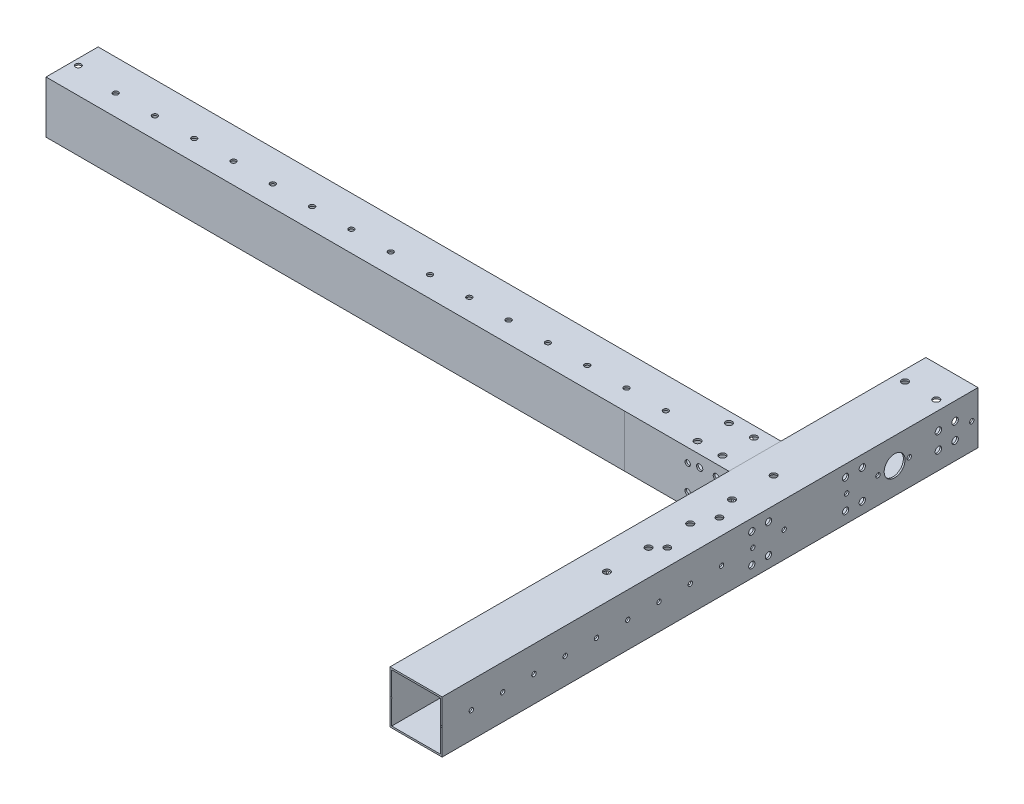
SolidWorks part; units mm, degrees
material "6061 合金"
ref_plane "前视基准面" through (0, 0, 0) normal (0, 0, 1) x (1, 0, 0)
ref_plane "上视基准面" through (0, 0, 0) normal (0, 1, 0) x (1, 0, 0)
ref_plane "右视基准面" through (0, 0, 0) normal (1, 0, 0) x (0, 0, -1)
sketch3d "3D草图1"
  line L0 (0, 0, -82) -> (0, 0, 175)
  line L1 (0, 0, 0) -> (-340, 0, 0)
  dimension "D1" = 175
  dimension "D2" = 340
  dimension "D3" = 82
other "方形管 20X20X1(1)"
ref_plane "基准面1" through (0, 0, 0) normal (-1, 0, 0) x (0, 0, 1)
sketch "草图1" plane through (0, 0, 0) normal (-1, 0, 0) x (0, 0, 1)
  line L0 (-11.7, 11.7) -> (11.7, 11.7)
  line L1 (-12.5, 12.5) -> (12.5, 12.5)
  line L2 (-12.5, 12.5) -> (-12.5, -12.5)
  line L3 (-12.5, -12.5) -> (12.5, -12.5)
  line L4 (12.5, 12.5) -> (12.5, -12.5)
  line L5 (-12.5, 12.5) -> (12.5, -12.5) construction
  line L6 (-12.5, -12.5) -> (12.5, 12.5) construction
  line L7 (11.7, 11.7) -> (11.7, -11.7)
  line L8 (-11.7, -11.7) -> (11.7, -11.7)
  line L9 (-11.7, 11.7) -> (-11.7, -11.7)
  point P0 (0, 0)
  point P10 (0, 0)
  dimension "D1" = 25
  dimension "D2" = 0.8
sketch "草图6" plane through (12.5, 0, 0) normal (1, 0, 0) x (0, 0, -1)
  line L0 (-236, 0) -> (-251, 0) construction
  line L1 (64, 0) -> (67.4326, 0) construction
  line L2 (82, 12.5) -> (82, -12.5) construction
  line L3 (12.5, 12.5) -> (12.5, -12.5) construction
  circle A0 centre (-236, 0) radius 1.05
  circle A1 centre (-221, 0) radius 1.05
  circle A2 centre (-206, 0) radius 1.05
  circle A3 centre (-191, 0) radius 1.05
  circle A4 centre (-176, 0) radius 1.05
  circle A5 centre (-161, 0) radius 1.05
  circle A6 centre (-146, 0) radius 1.05
  circle A7 centre (-131, 0) radius 1.05
  circle A8 centre (-116, 0) radius 1.05
  circle A9 centre (-101, 0) radius 1.05
  circle A10 centre (-86, 0) radius 1.05
  circle A11 centre (-71, 0) radius 1.05
  circle A12 centre (-56, 0) radius 1.05
  circle A13 centre (-41, 0) radius 1.05
  circle A14 centre (-26, 0) radius 1.05
  circle A15 centre (-11, 0) radius 1.05
  circle A16 centre (4, 0) radius 1.05 construction
  circle A17 centre (19, 0) radius 1.05
  circle A18 centre (34, 0) radius 1.05
  circle A19 centre (49, 0) radius 1.05
  circle A20 centre (64, 0) radius 1.05 construction
  circle A21 centre (79, 0) radius 1.05
  circle A22 centre (94, 0) radius 1.05
  circle A23 centre (109, 0) radius 1.05
  circle A24 centre (124, 0) radius 1.05
  circle A25 centre (139, 0) radius 1.05
  circle A26 centre (154, 0) radius 1.05
  circle A27 centre (169, 0) radius 1.05
  circle A29 centre (-251, 0) radius 1.05
  circle A35 centre (-266, 0) radius 1.05
  circle A36 centre (-281, 0) radius 1.05
  circle A37 centre (-296, 0) radius 1.05
  circle A38 centre (71, 4) radius 1.55
  circle A39 centre (63, 4) radius 1.55
  circle A40 centre (71, -4) radius 1.55
  circle A41 centre (63, -4) radius 1.55
  circle A42 centre (42, 0) radius 5
  dimension "D2" = 2.1
  dimension "D7" = 8
  dimension "D10" = 3.1
  dimension "D11" = 10
  dimension "D1" = 3
  dimension "D4" = 15
  dimension "D5" = 5
  dimension "D6" = 15
  dimension "D9" = 4
  dimension "D8" = 8
  dimension "D12" = 29.5
  dimension "D3" = 28
extrude "切除-拉伸5" cut sketch "草图6" against normal through all
sketch "草图7" plane through (0, -12.5, 0) normal (0, -1, 0) x (1, 0, 0)
  line L0 (12.5, 46.5) -> (0, 46.5) construction
  line L1 (12.5, 175) -> (12.5, -82) construction
  circle A0 centre (4.5, 34) radius 1.5
  circle A1 centre (4.5, 59) radius 1.5
  dimension "D2" = 3
  dimension "D1" = 25
  dimension "D3" = 8
extrude "切除-拉伸6" cut sketch "草图7" against normal through all
sketch "草图8" plane through (0, 12.5, 0) normal (0, 1, 0) x (1, 0, 0)
  circle A0 centre (-316.6062, -2.5) radius 1.25 construction
  circle A1 centre (-297.7566, -2.5) radius 1.25 construction
  circle A2 centre (-278.9071, -2.5) radius 1.25 construction
  circle A3 centre (-260.0575, -2.5) radius 1.25 construction
  circle A4 centre (-241.2079, -2.5) radius 1.25 construction
  circle A5 centre (-222.3584, -2.5) radius 1.25 construction
  circle A6 centre (-203.5088, -2.5) radius 1.25 construction
  circle A7 centre (-184.6593, -2.5) radius 1.25 construction
  circle A8 centre (-165.8097, -2.5) radius 1.25 construction
  circle A9 centre (-146.9602, -2.5) radius 1.25 construction
  circle A10 centre (-128.1106, -2.5) radius 1.25 construction
  circle A11 centre (-316.6062, -2.5) radius 1.25
  circle A12 centre (-297.7566, -2.5) radius 1.25
  circle A13 centre (-278.9071, -2.5) radius 1.25
  circle A14 centre (-260.0575, -2.5) radius 1.25
  circle A15 centre (-241.2079, -2.5) radius 1.25
  circle A16 centre (-222.3584, -2.5) radius 1.25
  circle A17 centre (-203.5088, -2.5) radius 1.25
  circle A18 centre (-184.6593, -2.5) radius 1.25
  circle A19 centre (-165.8097, -2.5) radius 1.25
  circle A20 centre (-146.9602, -2.5) radius 1.25
  circle A21 centre (-128.1106, -2.5) radius 1.25
  circle A22 centre (-71.5619, -2.5) radius 1.25 construction
  circle A23 centre (-90.4115, -2.5) radius 1.25 construction
  circle A24 centre (-109.2611, -2.5) radius 1.25 construction
  circle A25 centre (-71.5619, -2.5) radius 1.25
  circle A26 centre (-90.4115, -2.5) radius 1.25
  circle A27 centre (-109.2611, -2.5) radius 1.25
  circle A28 centre (-52.7124, -2.5) radius 1.25 construction
  circle A29 centre (-52.7124, -2.5) radius 1.25
  circle A30 centre (-32.5, 7.5) radius 1.55 construction
  circle A31 centre (-32.5, -7.5) radius 1.55 construction
  circle A32 centre (-20.5, 7.5) radius 1.55 construction
  circle A33 centre (-20.5, -7.5) radius 1.55 construction
  circle A34 centre (-32.5, 7.5) radius 1.55
  circle A35 centre (-32.5, -7.5) radius 1.55
  circle A36 centre (-20.5, 7.5) radius 1.55
  circle A37 centre (-20.5, -7.5) radius 1.55
  circle A39 centre (0, -63.5) radius 1.55 construction
  circle A40 centre (0, -43.5) radius 1.55 construction
  circle A41 centre (0, -23.5) radius 1.55 construction
  circle A42 centre (0, -3.5) radius 1.55 construction
  circle A43 centre (0, -83.5) radius 1.55
  circle A44 centre (0, -63.5) radius 1.55
  circle A45 centre (0, -43.5) radius 1.55
  circle A46 centre (0, -23.5) radius 1.55
  circle A47 centre (0, -3.5) radius 1.55
  circle A48 centre (-337, 0) radius 1.35 construction
  circle A49 centre (-337, 0) radius 1.35
extrude "切除-拉伸7" cut sketch "草图8" against normal through all
sketch "草图9" plane through (0, 0, 12.5) normal (0, 0, 1) x (1, 0, 0)
  circle A0 centre (-18.5, 7) radius 1.5 construction
  circle A1 centre (-18.5, -7) radius 1.5 construction
  circle A2 centre (-26.5, -7) radius 1.5 construction
  circle A3 centre (-26.5, 7) radius 1.5 construction
  circle A4 centre (-18.5, 7) radius 1.5
  circle A5 centre (-18.5, -7) radius 1.5
  circle A6 centre (-26.5, -7) radius 1.5
  circle A7 centre (-26.5, 7) radius 1.5
extrude "切除-拉伸8" cut sketch "草图9" against normal through all
sketch "草图10" plane through (0, 0, 12.5) normal (0, 0, 1) x (1, 0, 0)
  circle A0 centre (-32.25, 6) radius 1.3 construction
  circle A1 centre (-32.25, -6) radius 1.3 construction
  circle A2 centre (-32.25, 6) radius 1.3
  circle A3 centre (-32.25, -6) radius 1.3
extrude "切除-拉伸9" cut sketch "草图10" against normal through all
sketch "草图11" plane through (-12.5, 0, 0) normal (-1, 0, 0) x (0, 0, 1)
  circle A0 centre (18.5, -7) radius 1.5 construction
  circle A1 centre (26.5, -7) radius 1.5 construction
  circle A2 centre (26.5, 7) radius 1.5 construction
  circle A3 centre (18.5, 7) radius 1.5 construction
  circle A4 centre (18.5, -7) radius 1.5
  circle A5 centre (26.5, -7) radius 1.5
  circle A6 centre (26.5, 7) radius 1.5
  circle A7 centre (18.5, 7) radius 1.5
  circle A8 centre (-26.5, -7) radius 1.5 construction
  circle A9 centre (-18.5, -7) radius 1.5 construction
  circle A10 centre (-18.5, 7) radius 1.5 construction
  circle A11 centre (-26.5, 7) radius 1.5 construction
  circle A12 centre (-26.5, -7) radius 1.5
  circle A13 centre (-18.5, -7) radius 1.5
  circle A14 centre (-18.5, 7) radius 1.5
  circle A15 centre (-26.5, 7) radius 1.5
extrude "切除-拉伸10" cut sketch "草图11" against normal through all
sketch "草图12" plane through (0, 12.5, 0) normal (0, 1, 0) x (1, 0, 0)
  line L0 (0, 82) -> (0, 60.2718) construction
  line L1 (12.5, 82) -> (-12.5, 82) construction
  circle A0 centre (-7.5, 67) radius 1.55
  circle A1 centre (7.5, 67) radius 1.55
  dimension "D2" = 3.1
  dimension "D1" = 15
  dimension "D3" = 15
extrude "切除-拉伸11" cut sketch "草图12" against normal through all
sketch "草图13" plane through (0, 0, 12.5) normal (0, 0, 1) x (1, 0, 0)
  line L1 (-62.5, 12.5) -> (-12.5, 12.5)
  line L2 (-62.5, 12.5) -> (-62.5, -12.5)
  line L3 (-62.5, -12.5) -> (-12.5, -12.5)
  line L4 (-12.5, 12.5) -> (-12.5, -12.5)
  line L5 (-62.5, 12.5) -> (-12.5, -12.5) construction
  line L6 (-62.5, -12.5) -> (-12.5, 12.5) construction
  point P0 (-37.5, 0)
  dimension "D1" = 50
extrude "切除-拉伸12" cut sketch "草图13" against normal blind 0.01
